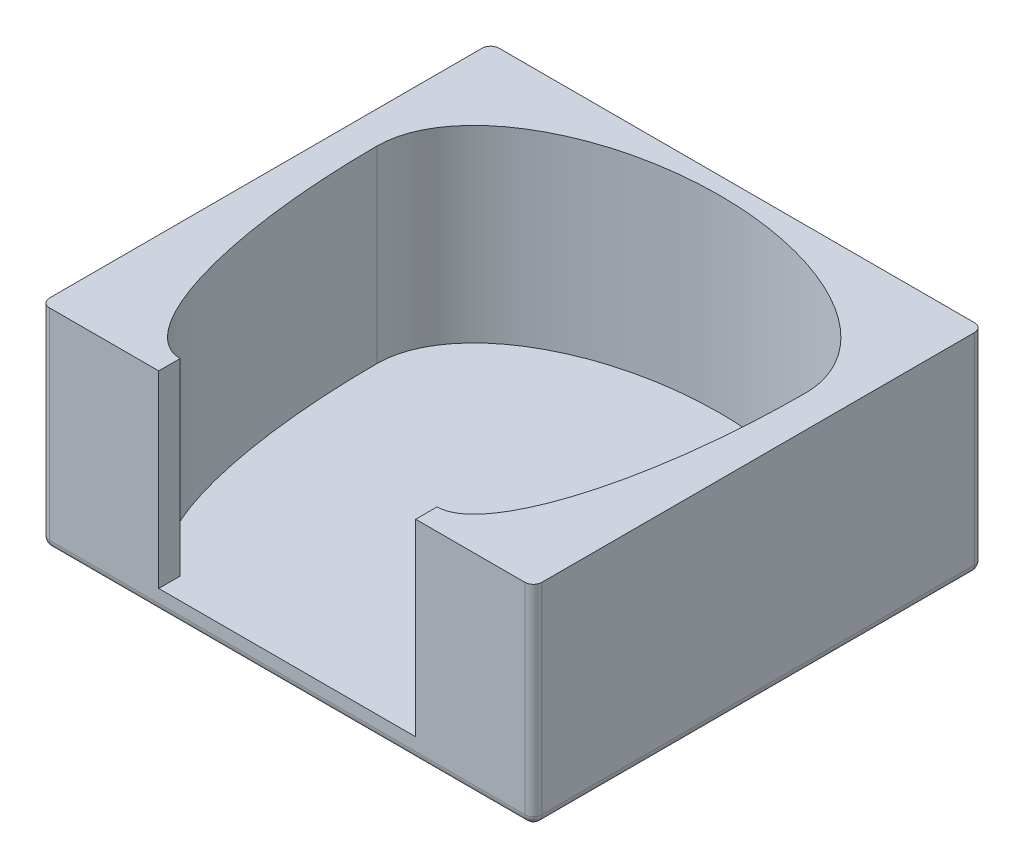
SolidWorks part; units mm, degrees
ref_plane "Front Plane" through (0, 0, 0) normal (0, 0, 1) x (1, 0, 0)
ref_plane "Top Plane" through (0, 0, 0) normal (0, 1, 0) x (1, 0, 0)
ref_plane "Right Plane" through (0, 0, 0) normal (1, 0, 0) x (0, 0, -1)
sketch "Sketch2" plane through (0, 0, 0) normal (0, 1, 0) x (1, 0, 0)
  line L1 (28.75, -26.25) -> (-28.75, -26.25)
  line L2 (28.75, -26.25) -> (28.75, 26.25)
  line L3 (28.75, 26.25) -> (-28.75, 26.25)
  line L4 (-28.75, -26.25) -> (-28.75, 26.25)
  line L5 (28.75, -26.25) -> (-28.75, 26.25) construction
  line L6 (28.75, 26.25) -> (-28.75, -26.25) construction
  point P0 (0, 0)
  dimension "D1" = 57.5
  dimension "D2" = 52.5
extrude "Boss-Extrude1" add sketch "Sketch2" along normal blind 2.5
sketch "Sketch3" plane through (0, 2.5, 0) normal (0, 1, 0) x (1, 0, 0)
  line L0 (-25, 9.25) -> (-15, 9.25) construction
  line L2 (-15, -23.75) -> (-15, 9.25)
  line L3 (-15, 9.25) -> (15, 9.25)
  line L4 (15, -23.75) -> (15, 9.25)
  line L5 (-28.75, 26.25) -> (-28.75, -26.25) construction
  line L7 (15, 9.25) -> (25, 9.25) construction
  line L8 (-15, -23.75) -> (-15, -26.25)
  line L9 (-28.75, -26.25) -> (28.75, -26.25) construction
  line L10 (15, -23.75) -> (15, -26.25)
  line L11 (28.75, -26.25) -> (28.75, 26.25) construction
  ellipse E0 centre (-15, 9.25) end of major axis (-15, -23.75) minor radius 10 (-25, 9.25) -> (-15, -23.75) ccw
  ellipse E1 centre (15, 9.25) end of major axis (15, -23.75) minor radius 10 (15, -23.75) -> (25, 9.25) ccw
  ellipse E2 centre (0, 9.25) end of major axis (-25, 9.25) minor radius 15 (-25, 9.25) -> (25, 9.25) cw
  point P0 (0, 0)
  dimension "D1" = 30
  dimension "D2" = 33
  dimension "D3" = 10
  dimension "D4" = 15
  dimension "D6" = 3.75
  dimension "D7" = 3.75
extrude "Boss-Extrude2" add sketch "Sketch3" along normal blind 22
fillet "Fillet1" radius 1 8 edges at (-28.75, 0, 0) (-28.75, 12.25, -26.25) (0, 0, -26.25) (28.75, 12.25, -26.25) (28.75, 0, 0) (28.75, 12.25, 26.25) (0, 0, 26.25) (-28.75, 12.25, 26.25)
